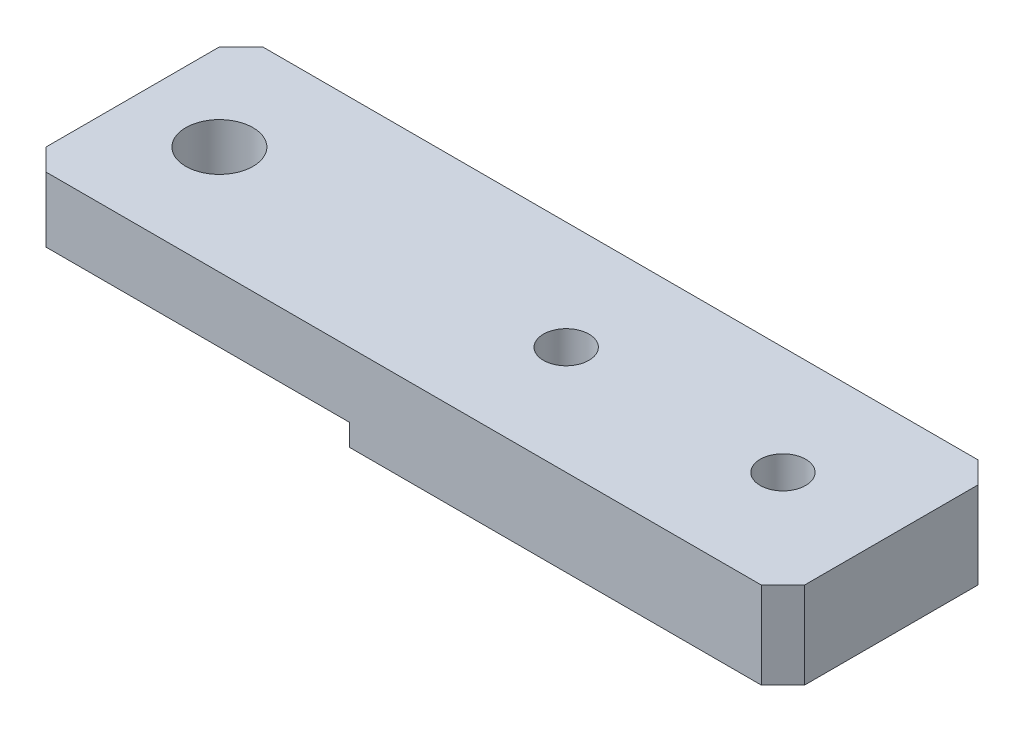
SolidWorks part; units mm, degrees
ref_plane "前视基准面" through (0, 0, 0) normal (0, 0, 1) x (1, 0, 0)
ref_plane "上视基准面" through (0, 0, 0) normal (0, 1, 0) x (1, 0, 0)
ref_plane "右视基准面" through (0, 0, 0) normal (1, 0, 0) x (0, 0, -1)
other "Configuration Table"
sketch "草图1" plane through (0, 0, 0) normal (0, 0, 1) x (1, 0, 0)
  line L0 (0, 4) -> (0, 10)
  line L1 (0, 10) -> (70, 10)
  line L2 (70, 10) -> (70, 2)
  line L3 (70, 2) -> (30, 2)
  line L4 (0, 4) -> (30, 4)
  line L5 (30, 4) -> (30, 2)
  line L6 (0, 4) -> (0, 0) construction
  dimension "D1" = 8
  dimension "D2" = 10
  dimension "D3" = 70
  dimension "D4" = 6
  dimension "D5" = 30
extrude "凸台-拉伸1" add sketch "草图1" along normal mid plane 20
sketch "草图3" plane through (0, 4, 0) normal (0, -1, 0) x (1, 0, 0)
  circle A0 centre (8, 0) radius 5
  dimension "D1" = 10
  dimension "D2" = 8
extrude "凸台-拉伸2" add sketch "草图3" along normal blind 2
chamfer "倒角1" distance 2 angle 45 2 edges at (0, 7, -10) (0, 7, 10)
chamfer "倒角2" distance 2 angle 45 2 edges at (70, 6, -10) (70, 6, 10)
sketch "草图4" plane through (0, 2, 0) normal (0, -1, 0) x (1, 0, 0)
  line L0 (70, 8) -> (70, -8) construction
  circle A0 centre (40, 0) radius 2.1
  circle A1 centre (60, 0) radius 2.1
  circle A2 centre (8, 0) radius 3.1
  dimension "D2" = 6.2
  dimension "D3" = 4.2
  dimension "D4" = 4.2
  dimension "D1" = 20
  dimension "D5" = 10
extrude "切除-拉伸1" cut sketch "草图4" against normal through all
fillet "圆角1" radius 1 1 edges at (8, 4, 5)
